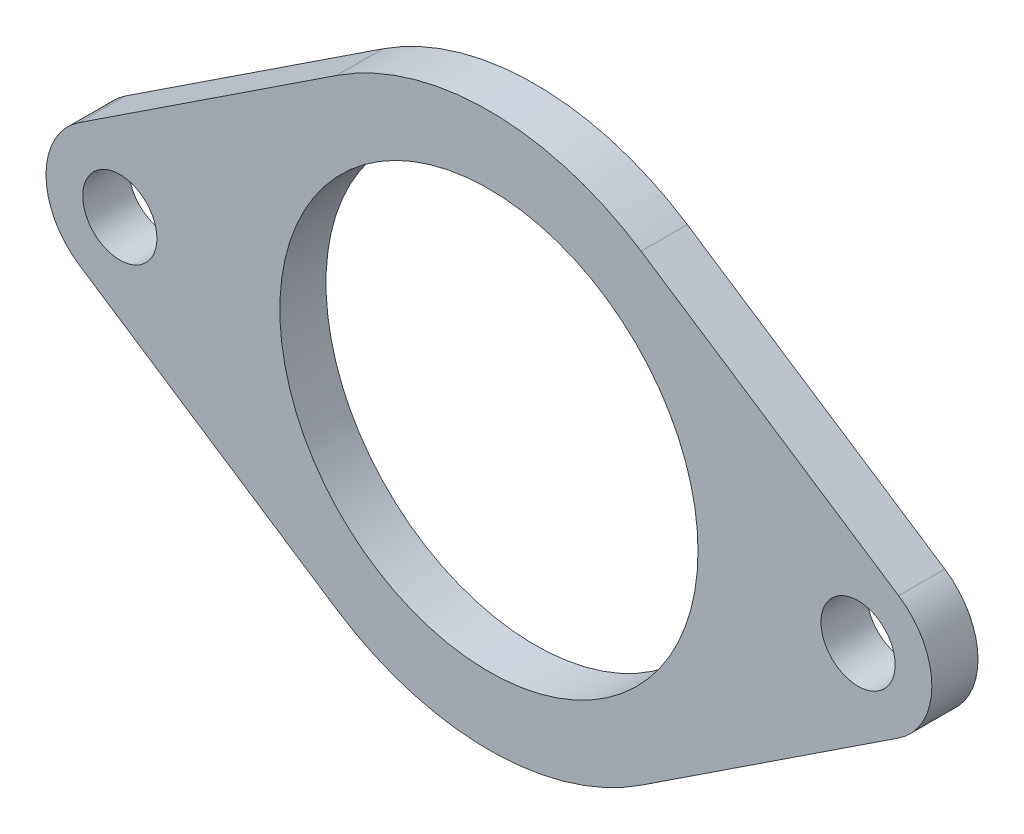
SolidWorks part; units mm, degrees
ref_plane "Front Plane" through (0, 0, 0) normal (0, 0, 1) x (1, 0, 0)
ref_plane "Top Plane" through (0, 0, 0) normal (0, 1, 0) x (1, 0, 0)
ref_plane "Right Plane" through (0, 0, 0) normal (1, 0, 0) x (0, 0, -1)
sketch "Sketch1" plane through (0, 0, 0) normal (0, 0, 1) x (1, 0, 0)
  line L0 (-10.4775, 15.9099) -> (-28.194, 4.2426)
  line L1 (10.4775, 15.9099) -> (28.194, 4.2426)
  line L2 (28.194, -4.2426) -> (10.4775, -15.9099)
  line L3 (-10.4775, -15.9099) -> (-28.194, -4.2426)
  circle A0 centre (0, 0) radius 14.3891
  circle A1 centre (-25.4, 0) radius 2.5527
  circle A2 centre (25.4, 0) radius 2.5527
  circle A3 centre (0, 0) radius 19.05 construction
  circle A4 centre (25.4, 0) radius 5.08 construction
  circle A5 centre (-25.4, 0) radius 5.08 construction
  arc A6 (-10.4775, 15.9099) -> (10.4775, 15.9099) centre (0, 0) cw
  arc A7 (28.194, 4.2426) -> (28.194, -4.2426) centre (25.4, 0) cw
  arc A8 (10.4775, -15.9099) -> (-10.4775, -15.9099) centre (0, 0) cw
  arc A9 (-28.194, 4.2426) -> (-28.194, -4.2426) centre (-25.4, 0) ccw
  dimension "D1" = 28.7782
  dimension "D2" = 5.1054
  dimension "D3" = 5.1054
  dimension "D6" = 38.1
  dimension "D7" = 10.16
  dimension "D4" = 25.4
  dimension "D5" = 25.4
extrude "Boss-Extrude1" add sketch "Sketch1" along normal blind 3.175
